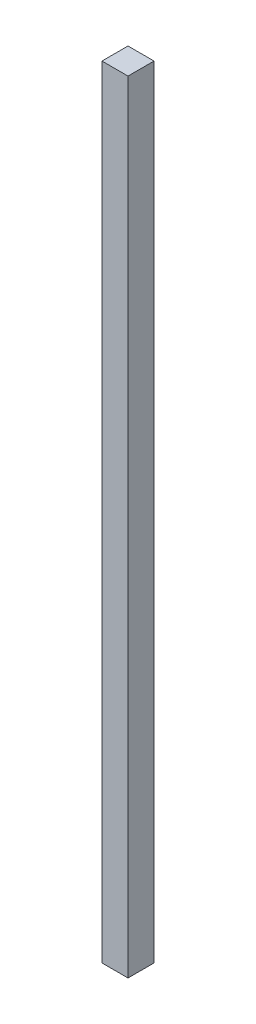
SolidWorks part; units mm, degrees
ref_plane "Front Plane" through (0, 0, 0) normal (0, 0, 1) x (1, 0, 0)
ref_plane "Top Plane" through (0, 0, 0) normal (0, 1, 0) x (1, 0, 0)
ref_plane "Right Plane" through (0, 0, 0) normal (1, 0, 0) x (0, 0, -1)
sketch "Sketch1" plane through (0, 0, 0) normal (0, 1, 0) x (1, 0, 0)
  line L1 (-2.5, 2.5) -> (2.5, 2.5)
  line L2 (-2.5, 2.5) -> (-2.5, -2.5)
  line L3 (-2.5, -2.5) -> (2.5, -2.5)
  line L4 (2.5, 2.5) -> (2.5, -2.5)
  line L5 (-2.5, 2.5) -> (2.5, -2.5) construction
  line L6 (-2.5, -2.5) -> (2.5, 2.5) construction
  point P0 (0, 0)
  dimension "D1" = 5
  dimension "1cm" = 5
extrude "Boss-Extrude1" add sketch "Sketch1" along normal blind 150
